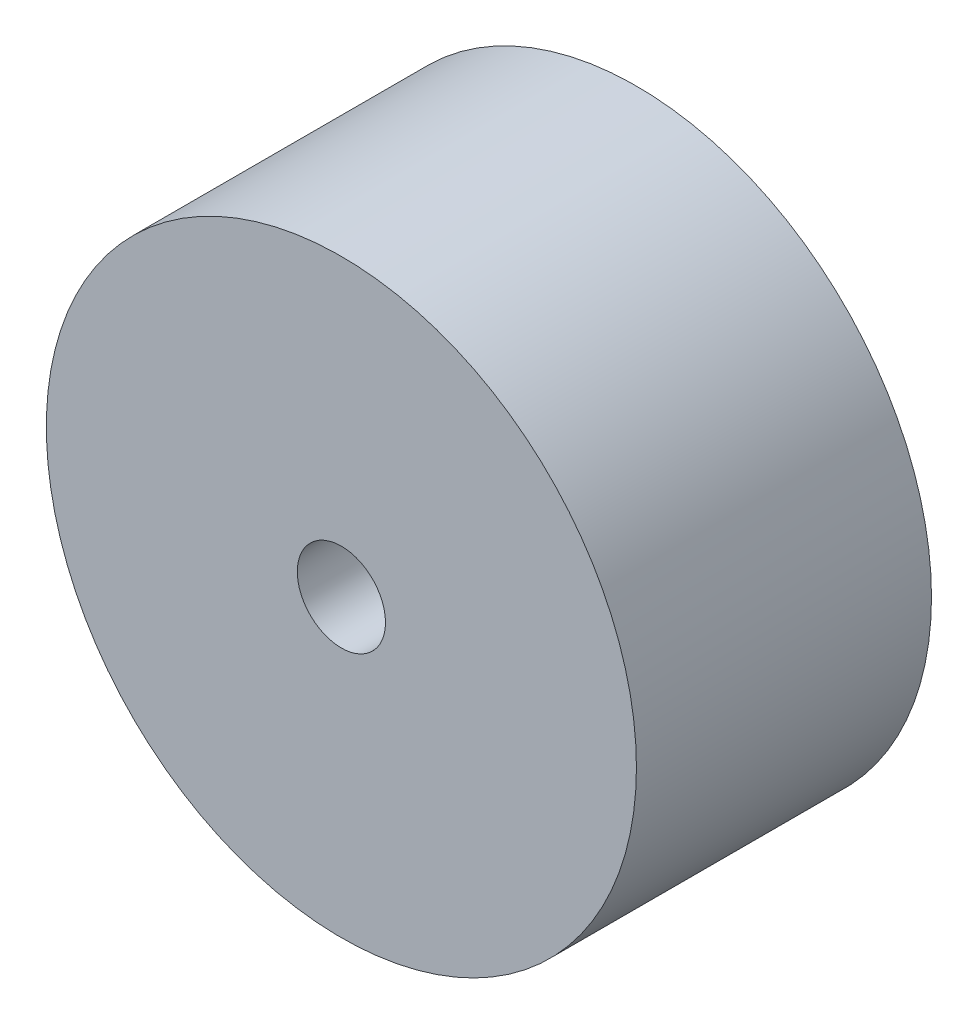
SolidWorks part; units mm, degrees
material "Copper"
ref_plane "Front Plane" through (0, 0, 0) normal (0, 0, 1) x (1, 0, 0)
ref_plane "Top Plane" through (0, 0, 0) normal (0, 1, 0) x (1, 0, 0)
ref_plane "Right Plane" through (0, 0, 0) normal (1, 0, 0) x (0, 0, -1)
sketch "Sketch1" plane through (0, 0, 0) normal (0, 0, 1) x (1, 0, 0)
  circle A0 centre (0, 0) radius 12.7
  dimension "D1" = 25.4
extrude "Boss-Extrude1" add sketch "Sketch1" along normal blind 12.7
hole_wizard "#6 Clearance Hole1" positions "Sketch2" profile "Sketch3" hole size "#6" standard "ANSI Inch" end condition through all
sketch "Sketch2" plane through (0, 0, 12.7) normal (0, 0, 1) x (1, 0, 0)
  point P0 (0, 0)
sketch "Sketch3" plane through (0, 0, 12.7) normal (1, 0, 0) x (0, -1, 0)
  line L0 (0, 0) -> (0, 12.7)
  line L1 (0, 12.7) -> (1.8986, 12.7)
  line L2 (1.8986, 12.7) -> (1.8986, 0)
  line L5 (1.8986, 0) -> (0, 0)
  line L11 (0, -6.35) -> (0, 107.95) construction
  dimension "Thru Hole Dia." = 3.7973
  dimension "Thru Hole Depth" = 12.7
